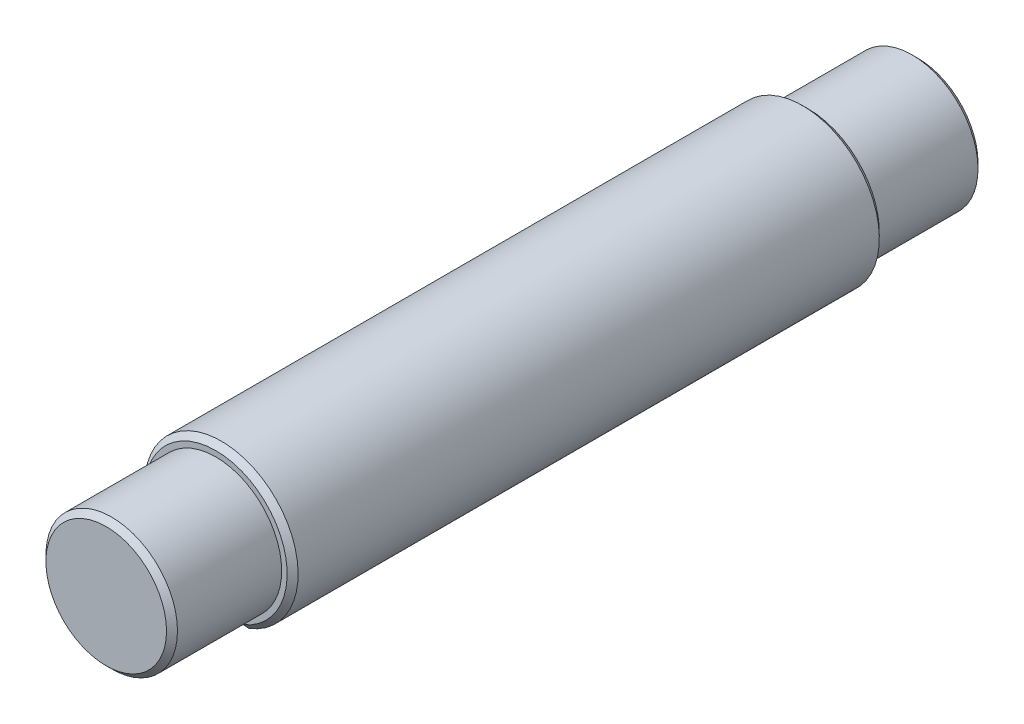
SolidWorks part; units mm, degrees
material "镀铬不锈钢"
ref_plane "前视基准面" through (0, 0, 0) normal (0, 0, 1) x (1, 0, 0)
ref_plane "上视基准面" through (0, 0, 0) normal (0, 1, 0) x (1, 0, 0)
ref_plane "右视基准面" through (0, 0, 0) normal (1, 0, 0) x (0, 0, -1)
sketch "Sketch1" plane through (0, 0, 0) normal (0, 0, 1) x (1, 0, 0)
  circle A0 centre (0, 0) radius 7
  dimension "D1" = 14
extrude "Extrude1" add sketch "Sketch1" along normal mid plane 74
sketch "Sketch3" plane through (0, 0, 0) normal (0, 1, 0) x (1, 0, 0)
  line L0 (0, -27) -> (0, 27) construction
  line L1 (-2.5, -27) -> (-2.5, 27)
  line L2 (2.5, -27) -> (2.5, 27)
  arc A0 (-2.5, -27) -> (2.5, -27) centre (0, -27) ccw
  arc A1 (2.5, 27) -> (-2.5, 27) centre (0, 27) ccw
  point P2 (0, 0)
  dimension "D1" = 5
  dimension "D2" = 54
extrude "Extrude3" cut sketch "Sketch3" against normal through all from offset 4 offset against normal yes
sketch "Sketch4" plane through (0, 0, 37) normal (0, 0, 1) x (1, 0, 0)
  circle A0 centre (0, 0) radius 6
  circle A2 centre (0, 0) radius 7
  circle A3 centre (0, 0) radius 7
  dimension "D1" = 12
  dimension "D2" = 0
extrude "Extrude4" cut sketch "Sketch4" against normal blind 10
mirror "Mirror1" about plane through (0, 0, 0) normal (0, 0, 1) of "Extrude4"
chamfer "Chamfer1" distance 0.5 angle 45 4 edges at (6, 0, -37) (6, 0, 37) (0, 7, -27) (0, 7, 27)
